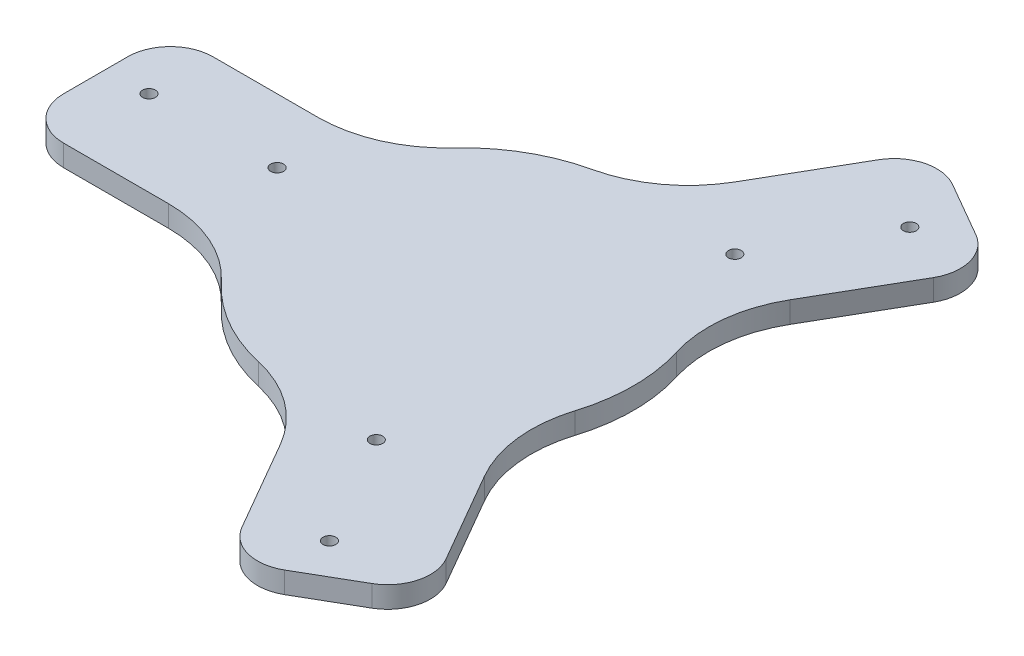
SolidWorks part; units mm, degrees
material "Pin"
ref_plane "Plan de face" through (0, 0, 0) normal (0, 0, 1) x (1, 0, 0)
ref_plane "Plan de dessus" through (0, 0, 0) normal (0, 1, 0) x (1, 0, 0)
ref_plane "Plan de droite" through (0, 0, 0) normal (1, 0, 0) x (0, 0, -1)
sketch "Esquisse1" plane through (0, 0, 0) normal (0, 1, 0) x (1, 0, 0)
  line L0 (40.8641, 35.7788) -> (53.1398, 57.0409)
  line L1 (-51.4174, -17.5) -> (-75.9687, -17.5)
  line L3 (-51.4174, 17.5) -> (-75.9687, 17.5)
  line L4 (-85.9687, -7.5) -> (-85.9687, 7.5)
  line L5 (36.4892, 78.2011) -> (49.4796, 70.7011)
  line L6 (10.5533, 53.2788) -> (22.8289, 74.5409)
  line L7 (10.5533, -53.2788) -> (22.8289, -74.5409)
  line L8 (49.4796, -70.7011) -> (36.4892, -78.2011)
  line L9 (40.8641, -35.7788) -> (53.1398, -57.0409)
  arc A0 (-29.3814, -27.1429) -> (-8.8157, -39.0164) centre (0, 0) ccw
  arc A1 (-75.9687, -17.5) -> (-85.9687, -7.5) centre (-75.9687, -7.5) cw
  arc A2 (-75.9687, 17.5) -> (-85.9687, 7.5) centre (-75.9687, 7.5) ccw
  arc A3 (-29.3814, -27.1429) -> (-51.4174, -17.5) centre (-51.4174, -47.5) ccw
  arc A4 (-29.3814, 27.1429) -> (-51.4174, 17.5) centre (-51.4174, 47.5) cw
  circle A5 centre (-75.9687, 2.5) radius 1.5
  circle A6 centre (-45.9687, 2.5) radius 1.5
  arc A7 (38.1971, 11.8736) -> (40.8641, 35.7788) centre (66.8449, 20.7788) cw
  arc A8 (53.1398, 57.0409) -> (49.4796, 70.7011) centre (44.4796, 62.0409) ccw
  arc A9 (22.8289, 74.5409) -> (36.4892, 78.2011) centre (31.4892, 69.5409) cw
  arc A10 (-8.8157, 39.0164) -> (10.5533, 53.2788) centre (-15.4275, 68.2788) ccw
  circle A11 centre (40.1494, 64.5409) radius 1.5
  circle A12 centre (25.1494, 38.5601) radius 1.5
  arc A13 (-8.8157, -39.0164) -> (10.5533, -53.2788) centre (-15.4275, -68.2788) cw
  arc A14 (22.8289, -74.5409) -> (36.4892, -78.2011) centre (31.4892, -69.5409) ccw
  arc A15 (53.1398, -57.0409) -> (49.4796, -70.7011) centre (44.4796, -62.0409) cw
  arc A16 (38.1971, -11.8736) -> (40.8641, -35.7788) centre (66.8449, -20.7788) ccw
  circle A17 centre (35.8193, -67.0409) radius 1.5
  circle A18 centre (20.8193, -41.0601) radius 1.5
  arc A19 (-8.8157, 39.0164) -> (-29.3814, 27.1429) centre (0, 0) ccw
  arc A20 (38.1971, -11.8736) -> (38.1971, 11.8736) centre (0, 0) ccw
  point P1 (-85.9687, 0)
  point P9 (-85.9687, -17.5)
  point P12 (-85.9687, 17.5)
  point P17 (-35.9687, 17.5)
  point P57 (0, 0)
  dimension "D1" = 80
  dimension "D4" = 10
  dimension "D5" = 30
  dimension "D6" = 3
  dimension "D7" = 3
  dimension "D2" = 35
  dimension "D3" = 50
  dimension "D8" = 30
  dimension "D9" = 10
  dimension "D10" = 20
  dimension "D11" = 3
extrude "Boss.-Extru.1" add sketch "Esquisse1" along normal blind 5
